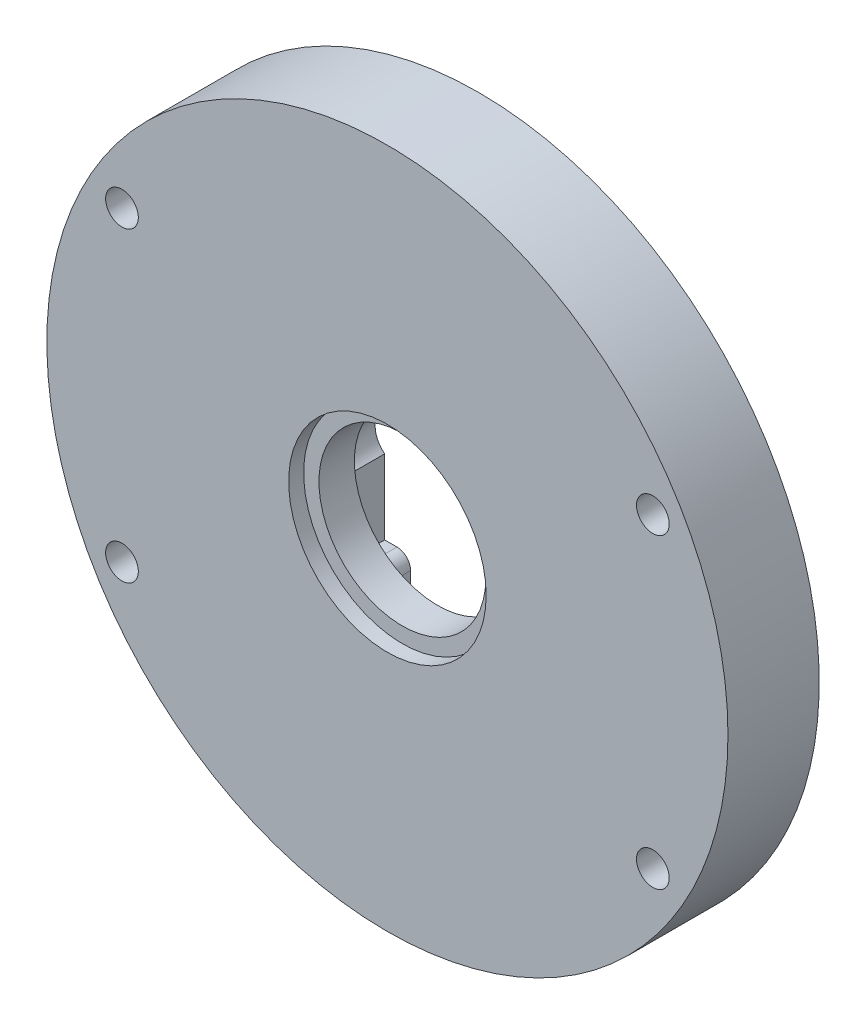
SolidWorks part; units mm, degrees
ref_plane "정면" through (0, 0, 0) normal (0, 0, 1) x (1, 0, 0)
ref_plane "윗면" through (0, 0, 0) normal (0, 1, 0) x (1, 0, 0)
ref_plane "우측면" through (0, 0, 0) normal (1, 0, 0) x (0, 0, -1)
sketch "스케치1" plane through (0, 0, 0) normal (0, 0, 1) x (1, 0, 0)
  line L0 (-5, -6.9) -> (-6.9, -6.9)
  line L2 (-5, -6.9) -> (-5, -24.4949)
  line L3 (0, -6.9) -> (0, -25) construction
  line L4 (5, -6.9) -> (5, -24.4949)
  line L6 (6.9, -6.9) -> (5, -6.9)
  line L7 (6.9, -6.9) -> (6.9, 6.9)
  line L8 (6.9, 6.9) -> (-6.9, 6.9)
  line L9 (-6.9, -6.9) -> (-6.9, 6.9)
  arc A0 (5, -24.4949) -> (-5, -24.4949) centre (0, 0) ccw
  circle A2 centre (0, 9.5) radius 2.1 construction
  circle A3 centre (0, 0) radius 9.5 construction
  point P1 (0, 6.9)
  point P15 (6.9, 0)
  point P19 (0, 0)
  point P28 (0, 0)
  dimension "D1" = 50
  dimension "D2" = 4.2
  dimension "D6" = 13.8
  dimension "D7" = 5
  dimension "D8" = 13.8
  dimension "D3" = 19
extrude "보스-돌출1" add sketch "스케치1" along normal blind 3
sketch "스케치11" plane through (0, 0, 3) normal (0, 0, 1) x (1, 0, 0)
  line L0 (5.8, 0) -> (-5.8, 0) construction
  line L1 (5.8, 0) -> (-5.8, 0) construction
  line L2 (5.8, -1.8) -> (-5.8, -1.8)
  line L3 (5.8, 1.8) -> (-5.8, 1.8)
  arc A0 (5.8, -1.8) -> (5.8, 1.8) centre (5.8, 0) ccw
  arc A1 (-5.8, 1.8) -> (-5.8, -1.8) centre (-5.8, 0) ccw
  point P4 (0, 0)
  point P6 (0, 0)
  dimension "D2" = 1.8
  dimension "D1" = 11.6
extrude "컷-돌출4" cut sketch "스케치11" against normal through all
sketch "스케치12" plane through (0, 0, 3) normal (0, 0, 1) x (1, 0, 0)
  circle A0 centre (0, 0) radius 25
  circle A1 centre (0, 0) radius 6.125
  dimension "D1" = 50
  dimension "D2" = 12.25
extrude "보스-돌출2" add sketch "스케치12" along normal blind 2.6
sketch "스케치13" plane through (0, 0, 5.6) normal (0, 0, 1) x (1, 0, 0)
  circle A0 centre (0, 0) radius 7.25
  circle A1 centre (0, 0) radius 25
  dimension "D1" = 14.5
  dimension "D2" = 50
extrude "보스-돌출3" add sketch "스케치13" along normal blind 1.1
sketch "스케치14" plane through (0, 0, 6.7) normal (0, 0, 1) x (1, 0, 0)
  line L0 (0, 0) -> (25, 0) construction
  line L1 (0, 0) -> (19.4856, 11.25) construction
  line L2 (0, 0) -> (19.4856, -11.25) construction
  line L3 (0, 0) -> (0, 25) construction
  circle A1 centre (19.4856, -11.25) radius 1.2
  circle A2 centre (0, 0) radius 25 construction
  circle A3 centre (19.4856, 11.25) radius 1.2
  circle A4 centre (-19.4856, 11.25) radius 1.2
  circle A5 centre (-19.4856, -11.25) radius 1.2
  point P17 (0, 0)
  dimension "D1" = 2.4
  dimension "D3" = 30
  dimension "D2" = 22.5
  dimension "D4" = 150
extrude "컷-돌출5" cut sketch "스케치14" against normal through all
fillet "필렛1" radius 1 2 edges at (-5, -6.9, 1.5) (5, -6.9, 1.5)
